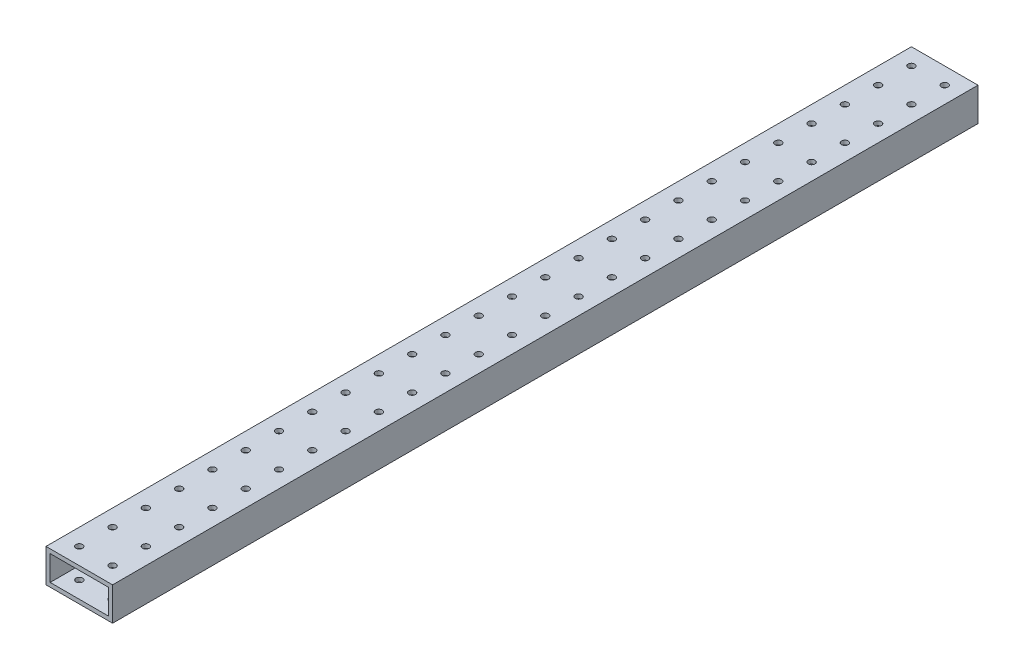
SolidWorks part; units mm, degrees
ref_plane "Front Plane" through (0, 0, 0) normal (0, 0, 1) x (1, 0, 0)
ref_plane "Top Plane" through (0, 0, 0) normal (0, 1, 0) x (1, 0, 0)
ref_plane "Right Plane" through (0, 0, 0) normal (1, 0, 0) x (0, 0, -1)
sketch "Sketch1" plane through (0, 0, 0) normal (0, 0, 1) x (1, 0, 0)
  line L1 (-38.1, -13.4893) -> (12.7, -13.4893)
  line L2 (-38.1, -13.4893) -> (-38.1, 11.9107)
  line L3 (-38.1, 11.9107) -> (12.7, 11.9107)
  line L4 (12.7, -13.4893) -> (12.7, 11.9107)
  line L5 (-38.1, -13.4893) -> (12.7, 11.9107) construction
  line L6 (-38.1, 11.9107) -> (12.7, -13.4893) construction
  point P0 (-12.7, -0.7893)
  dimension "D1" = 50.8
  dimension "D2" = 25.4
extrude "Boss-Extrude1" add sketch "Sketch1" along normal blind 660.4
sketch "Sketch2" plane through (0, 0, 660.4) normal (0, 0, 1) x (1, 0, 0)
  line L0 (-38.1, -13.4893) -> (12.7, -13.4893) construction
  line L5 (-34.925, -10.3143) -> (9.525, -10.3143)
  line L6 (-34.925, -10.3143) -> (-34.925, 8.7357)
  line L7 (-34.925, 8.7357) -> (9.525, 8.7357)
  line L8 (9.525, -10.3143) -> (9.525, 8.7357)
  line L9 (-34.925, -10.3143) -> (9.525, 8.7357) construction
  line L10 (-34.925, 8.7357) -> (9.525, -10.3143) construction
  line L11 (12.7, -13.4893) -> (12.7, 11.9107) construction
  point P0 (0, 0)
  point P1 (-12.7, -0.7893)
  dimension "D1" = 44.45
  dimension "D2" = 19.05
  dimension "D3" = 12.7
  dimension "D4" = 25.4
extrude "Cut-Extrude1" cut sketch "Sketch2" against normal up to surface (660.4 mm away) up to face at (-12.7, -0.7893, 0)
sketch "Sketch3" plane through (0, 11.9107, 0) normal (0, 1, 0) x (1, 0, 0)
  line L0 (12.7, -660.4) -> (-38.1, -660.4) construction
  line L1 (-38.1, -660.4) -> (-38.1, 0) construction
  circle A0 centre (-25.4, -647.7) radius 2.54
  circle A1 centre (0, -647.7) radius 2.54
  circle A2 centre (0, -622.3) radius 2.54
  circle A3 centre (0, -596.9) radius 2.54
  circle A4 centre (0, -571.5) radius 2.54
  circle A5 centre (0, -546.1) radius 2.54
  circle A6 centre (0, -520.7) radius 2.54
  circle A7 centre (0, -495.3) radius 2.54
  circle A8 centre (0, -469.9) radius 2.54
  circle A9 centre (0, -444.5) radius 2.54
  circle A10 centre (0, -419.1) radius 2.54
  circle A11 centre (0, -393.7) radius 2.54
  circle A12 centre (0, -368.3) radius 2.54
  circle A13 centre (0, -342.9) radius 2.54
  circle A14 centre (0, -317.5) radius 2.54
  circle A15 centre (0, -292.1) radius 2.54
  circle A16 centre (0, -266.7) radius 2.54
  circle A17 centre (0, -241.3) radius 2.54
  circle A18 centre (0, -215.9) radius 2.54
  circle A19 centre (0, -190.5) radius 2.54
  circle A20 centre (0, -165.1) radius 2.54
  circle A21 centre (0, -139.7) radius 2.54
  circle A22 centre (0, -114.3) radius 2.54
  circle A23 centre (0, -88.9) radius 2.54
  circle A24 centre (0, -63.5) radius 2.54
  circle A25 centre (0, -38.1) radius 2.54
  circle A26 centre (0, -12.7) radius 2.54
  circle A27 centre (-25.4, -622.3) radius 2.54
  circle A28 centre (-25.4, -596.9) radius 2.54
  circle A29 centre (-25.4, -571.5) radius 2.54
  circle A30 centre (-25.4, -546.1) radius 2.54
  circle A31 centre (-25.4, -520.7) radius 2.54
  circle A32 centre (-25.4, -495.3) radius 2.54
  circle A33 centre (-25.4, -469.9) radius 2.54
  circle A34 centre (-25.4, -444.5) radius 2.54
  circle A35 centre (-25.4, -419.1) radius 2.54
  circle A36 centre (-25.4, -393.7) radius 2.54
  circle A37 centre (-25.4, -368.3) radius 2.54
  circle A38 centre (-25.4, -342.9) radius 2.54
  circle A39 centre (-25.4, -317.5) radius 2.54
  circle A40 centre (-25.4, -292.1) radius 2.54
  circle A41 centre (-25.4, -266.7) radius 2.54
  circle A42 centre (-25.4, -241.3) radius 2.54
  circle A43 centre (-25.4, -215.9) radius 2.54
  circle A44 centre (-25.4, -190.5) radius 2.54
  circle A45 centre (-25.4, -165.1) radius 2.54
  circle A46 centre (-25.4, -139.7) radius 2.54
  circle A47 centre (-25.4, -114.3) radius 2.54
  circle A48 centre (-25.4, -88.9) radius 2.54
  circle A49 centre (-25.4, -63.5) radius 2.54
  circle A50 centre (-25.4, -38.1) radius 2.54
  circle A51 centre (-25.4, -12.7) radius 2.54
  dimension "D1" = 12.7
  dimension "D2" = 12.7
  dimension "D3" = 2
  dimension "D4" = 26
extrude "Cut-Extrude2" cut sketch "Sketch3" against normal up to surface (25.4 mm away) up to face at (-12.7, -13.4893, 330.2)
